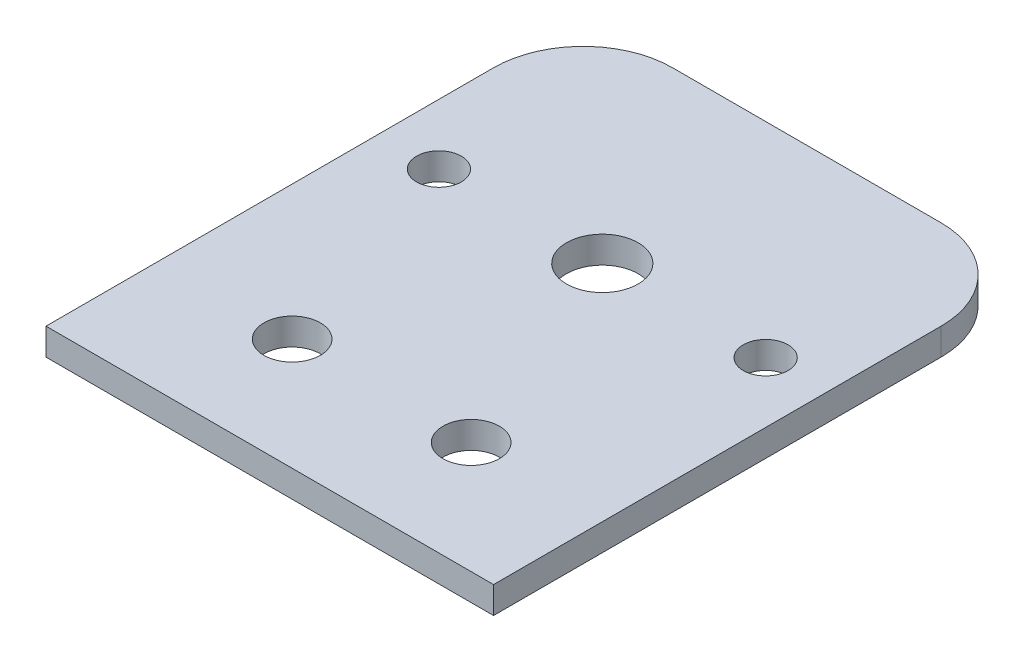
SolidWorks part; units mm, degrees
ref_plane "Alzado" through (0, 0, 0) normal (0, 0, 1) x (1, 0, 0)
ref_plane "Planta" through (0, 0, 0) normal (0, 1, 0) x (1, 0, 0)
ref_plane "Vista lateral" through (0, 0, 0) normal (1, 0, 0) x (0, 0, -1)
sketch "Croquis1" plane through (0, 0, 0) normal (0, 1, 0) x (1, 0, 0)
  line L0 (0, 0) -> (50000, 0) construction
  line L1 (0, 0) -> (0, 50000) construction
  line L8 (25, -37.15) -> (-25, -37.15)
  line L9 (25, -37.15) -> (25, 12.85)
  line L10 (15, 22.85) -> (-15, 22.85)
  line L11 (-25, -37.15) -> (-25, 12.85)
  circle A0 centre (0, 0) radius 4
  circle A3 centre (18.25, 0) radius 2.5
  arc A4 (-15, 22.85) -> (-25, 12.85) centre (-15, 12.85) ccw
  arc A5 (25, 12.85) -> (15, 22.85) centre (15, 12.85) ccw
  circle A6 centre (-18.25, 0) radius 2.5
  circle A7 centre (-10, -24.65) radius 3.15
  circle A8 centre (10, -24.65) radius 3.15
  point P15 (0, 22.85)
  point P20 (25, 22.85)
  dimension "D1" = 8
  dimension "D2" = 5
  dimension "D3" = 18.25
  dimension "D4" = 50
  dimension "D7" = 10
  dimension "D8" = 12.5
  dimension "D9" = 15
  dimension "D10" = 6.3
  dimension "D5" = 60
  dimension "D6" = 37.15
extrude "Saliente-Extruir1" add sketch "Croquis1" along normal blind 3
